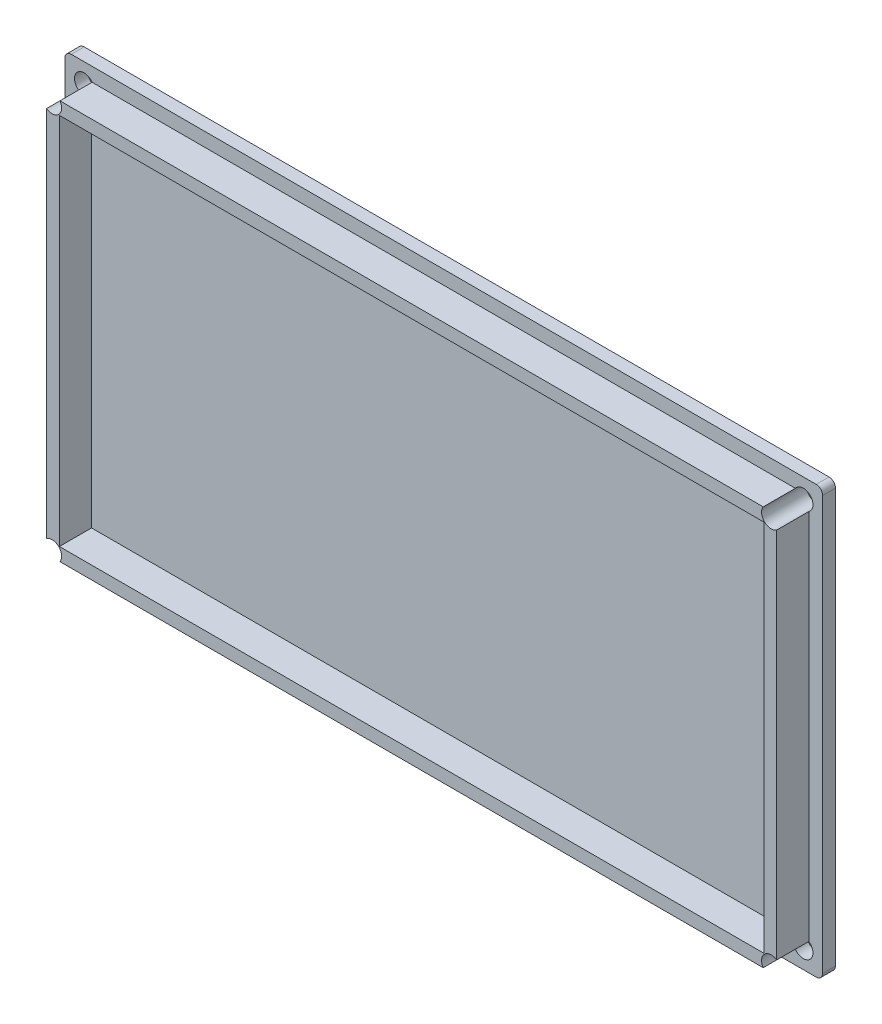
SolidWorks part; units mm, degrees
ref_plane "Front Plane" through (0, 0, 0) normal (0, 0, 1) x (1, 0, 0)
ref_plane "Top Plane" through (0, 0, 0) normal (0, 1, 0) x (1, 0, 0)
ref_plane "Right Plane" through (0, 0, 0) normal (1, 0, 0) x (0, 0, -1)
sketch "Sketch1" plane through (0, 0, 0) normal (0, 0, 1) x (1, 0, 0)
  line L1 (-55.6979, 33.2) -> (62.2021, 33.2)
  line L2 (-55.6979, 33.2) -> (-55.6979, -33.2)
  line L3 (-55.6979, -33.2) -> (62.2021, -33.2)
  line L4 (62.2021, 33.2) -> (62.2021, -33.2)
  line L5 (-55.6979, 33.2) -> (62.2021, -33.2) construction
  line L6 (-55.6979, -33.2) -> (62.2021, 33.2) construction
  point P0 (3.2521, 0)
  dimension "D1" = 66.4
  dimension "D2" = 117.9
extrude "Boss-Extrude1" add sketch "Sketch1" along normal blind 2
sketch "Sketch2" plane through (0, 0, 2) normal (0, 0, 1) x (1, 0, 0)
  line L0 (60.0521, -31.05) -> (60.0521, 31.05)
  line L1 (60.0521, 31.05) -> (-53.5479, 31.05)
  line L2 (-53.5479, 31.05) -> (-53.5479, -31.05)
  line L3 (-53.5479, -31.05) -> (60.0521, -31.05)
  line L12 (58.0521, -29.05) -> (58.0521, 29.05)
  line L13 (58.0521, 29.05) -> (-51.5479, 29.05)
  line L14 (-51.5479, 29.05) -> (-51.5479, -29.05)
  line L15 (-51.5479, -29.05) -> (58.0521, -29.05)
  line L16 (62.2021, 33.2) -> (-55.6979, 33.2) construction
  line L17 (-55.6979, 33.2) -> (-55.6979, -33.2) construction
  line L18 (-55.6979, -33.2) -> (62.2021, -33.2) construction
  line L19 (62.2021, -33.2) -> (62.2021, 33.2) construction
  dimension "D1" = 2.15
  dimension "D2" = 2.15
  dimension "D4" = 2.15
  dimension "D5" = 2.15
  dimension "D3" = 2
extrude "Boss-Extrude2" add sketch "Sketch2" along normal blind 5
sketch "Sketch3" plane through (0, 0, 0) normal (0, 0, -1) x (-1, 0, 0)
  line L0 (-62.2021, 33.2) -> (55.6979, 33.2) construction
  line L5 (-62.2021, -33.2) -> (-62.2021, 33.2) construction
  circle A0 centre (-59.2021, 30.2) radius 1.5
  dimension "D3" = 3
  dimension "D1" = 3
  dimension "D2" = 3
extrude "Cut-Extrude2" cut sketch "Sketch3" against normal through all both and the other way through all
mirror "Mirror2" about plane through (0, 0, 0) normal (0, 1, 0) of "Cut-Extrude2"
sketch "Sketch4" plane through (0, 0, 0) normal (0, 0, -1) x (-1, 0, 0)
  line L0 (-3.2521, 33.2) -> (-3.2521, -33.2) construction
  line L1 (-62.2021, 33.2) -> (55.6979, 33.2) construction
  line L2 (55.6979, -33.2) -> (-62.2021, -33.2) construction
  line L3 (-62.2021, 0) -> (55.6979, 0) construction
  line L4 (-62.2021, -33.2) -> (-62.2021, 33.2) construction
  line L5 (55.6979, 33.2) -> (55.6979, -33.2) construction
  dimension "D1" = 58.95
ref_plane "Plane1" through (3.2521, 0, 0) normal (1, 0, 0) x (0, 0, -1)
mirror "Mirror3" about plane through (0, 0, 0) normal (0, 1, 0) of "Cut-Extrude2" second plane through (3.2521, 0, 0) second plane normal (1, 0, 0)
fillet "Fillet1" radius 1 4 edges at (62.2021, -33.2, 1) (62.2021, 33.2, 1) (-55.6979, 33.2, 1) (-55.6979, -33.2, 1)
